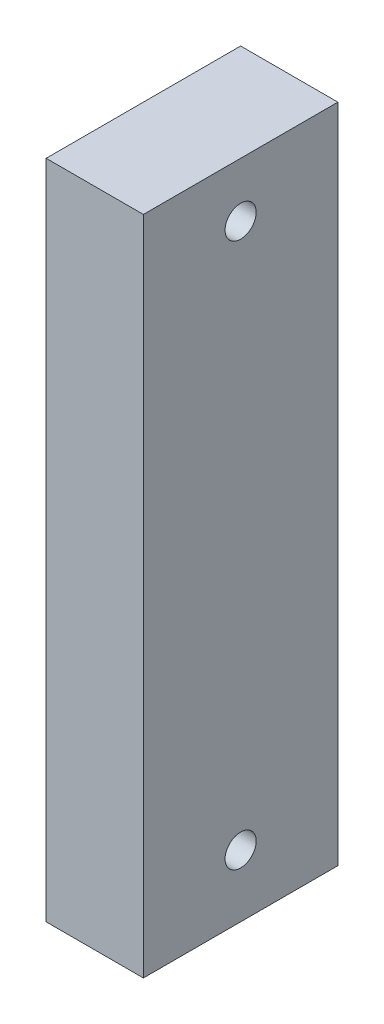
SolidWorks part; units mm, degrees
ref_plane "Front Plane" through (0, 0, 0) normal (0, 0, 1) x (1, 0, 0)
ref_plane "Top Plane" through (0, 0, 0) normal (0, 1, 0) x (1, 0, 0)
ref_plane "Right Plane" through (0, 0, 0) normal (1, 0, 0) x (0, 0, -1)
sketch "Sketch1" plane through (0, 0, 0) normal (0, 0, 1) x (1, 0, 0)
  line L1 (0, 0) -> (25, 0)
  line L2 (0, 0) -> (0, 170)
  line L3 (0, 170) -> (25, 170)
  line L4 (25, 0) -> (25, 170)
  dimension "D1" = 170
  dimension "D2" = 25
extrude "Boss-Extrude1" add sketch "Sketch1" along normal blind 50
sketch "Sketch3" plane through (0, 0, 0) normal (-1, 0, 0) x (0, 0, 1)
  line L0 (50, 0) -> (0, 0) construction
  line L1 (0, 170) -> (0, 0) construction
  line L2 (50, 170) -> (50, 0) construction
  circle A0 centre (25, 16) radius 4
  circle A1 centre (25, 156) radius 4
  dimension "D1" = 8
  dimension "D2" = 16
  dimension "D3" = 50
  dimension "D4" = 2
extrude "Cut-Extrude1" cut sketch "Sketch3" against normal through all
